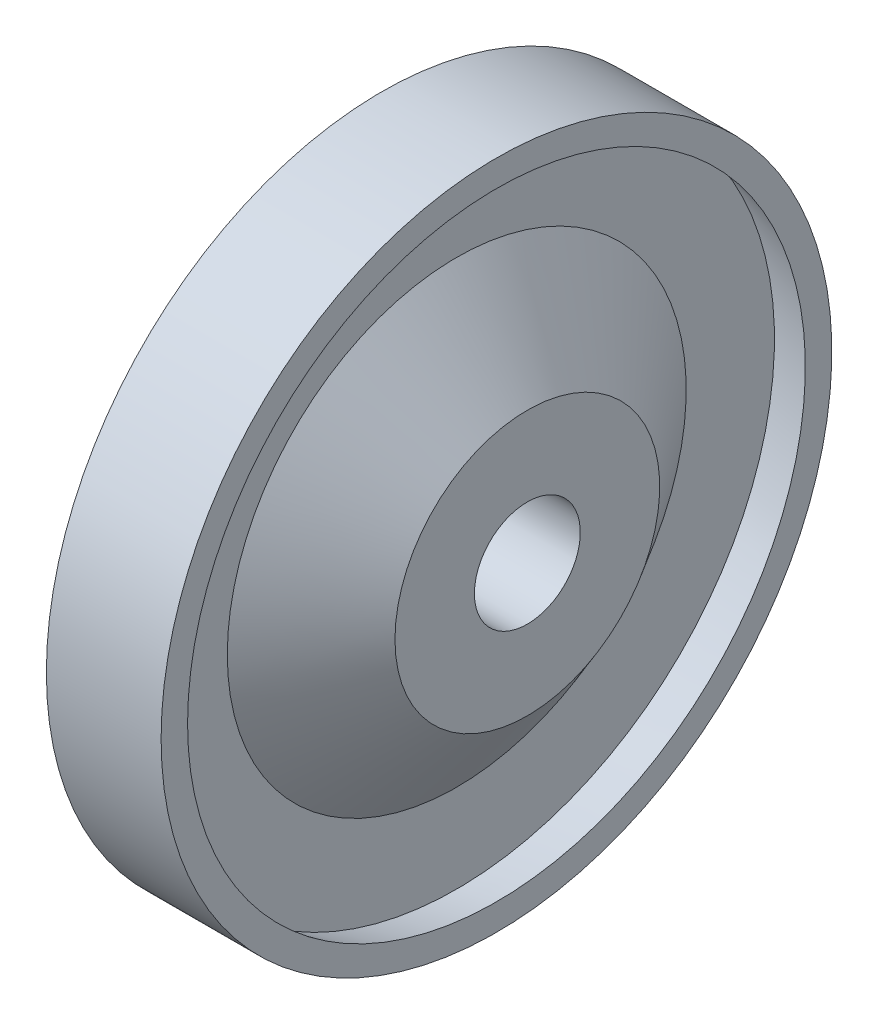
SolidWorks part; units mm, degrees
ref_plane "Front Plane" through (0, 0, 0) normal (0, 0, 1) x (1, 0, 0)
ref_plane "Top Plane" through (0, 0, 0) normal (0, 1, 0) x (1, 0, 0)
ref_plane "Right Plane" through (0, 0, 0) normal (1, 0, 0) x (0, 0, -1)
sketch "Sketch1" plane through (0, 0, 0) normal (0, 0, 1) x (1, 0, 0)
  line L0 (13, 76) -> (13, 70)
  line L1 (13, 70) -> (4, 72)
  line L2 (4, 72) -> (4, 52)
  line L3 (4, 52) -> (20, 30)
  line L4 (20, 30) -> (20, 12)
  line L5 (0, -55) -> (0, 55) construction
  line L6 (-20, 30) -> (-20, 12)
  line L7 (-4, 52) -> (-20, 30)
  line L8 (-4, 72) -> (-4, 52)
  line L9 (-13, 70) -> (-4, 72)
  line L10 (-13, 76) -> (-13, 70)
  line L11 (-13, 76) -> (13, 76)
  line L12 (-20, 12) -> (20, 12)
  line L13 (0, 0) -> (77.8011, 0) construction
  point P15 (-40.5244, 38.4549)
  point P18 (-32.0192, 13.823)
  point P19 (-30.6672, 32.6508)
  point P20 (-34.2957, 31.4897)
  point P21 (-51.7129, 30)
  point P22 (-38.3597, 30)
  point P23 (-23.8404, 74.101)
  point P24 (-13.6384, 101.8163)
  point P25 (-18.6352, 72)
  dimension "D1" = 12
  dimension "D2" = 30
  dimension "D3" = 40
  dimension "D4" = 60
  dimension "D5" = 70
  dimension "D6" = 76
  dimension "D7" = 26
  dimension "D8" = 8
  dimension "D9" = 40
revolve "Revolve1" add sketch "Sketch1" angle 360 about L13
